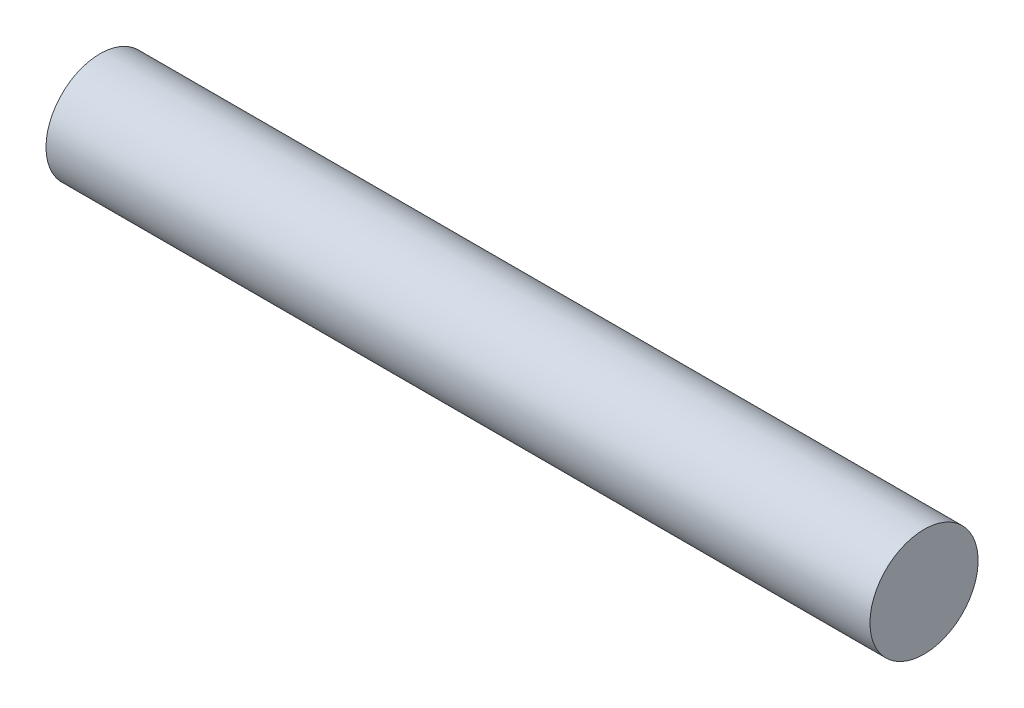
SolidWorks part; units mm, degrees
ref_plane "Front Plane" through (0, 0, 0) normal (0, 0, 1) x (1, 0, 0)
ref_plane "Top Plane" through (0, 0, 0) normal (0, 1, 0) x (1, 0, 0)
ref_plane "Right Plane" through (0, 0, 0) normal (1, 0, 0) x (0, 0, -1)
sketch "Sketch1" plane through (0, 0, 0) normal (1, 0, 0) x (0, 0, -1)
  circle A0 centre (0, 0) radius 5
extrude "Boss-Extrude1" add sketch "Sketch1" along normal blind 76.2
